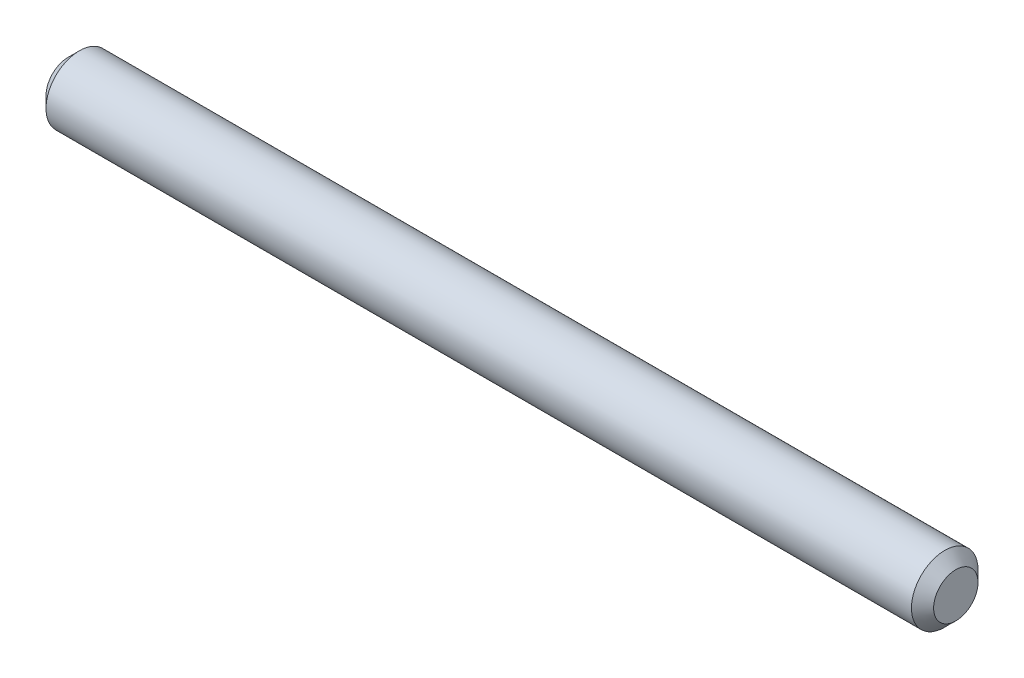
SolidWorks part; units mm, degrees
ref_plane "Płaszczyzna przednia" through (0, 0, 0) normal (0, 0, 1) x (1, 0, 0)
ref_plane "Płaszczyzna górna" through (0, 0, 0) normal (0, 1, 0) x (1, 0, 0)
ref_plane "Płaszczyzna prawa" through (0, 0, 0) normal (1, 0, 0) x (0, 0, -1)
sketch "Szkic1" plane through (0, 0, 0) normal (1, 0, 0) x (0, 0, -1)
  circle A0 centre (0, 0) radius 3
  dimension "D1" = 6
extrude "Dodanie-wyciągnięcie1" add sketch "Szkic1" along normal mid plane 80
chamfer "Sfazowanie1" distance 1 angle 45 2 edges at (-40, 0, -3) (40, 0, -3)
